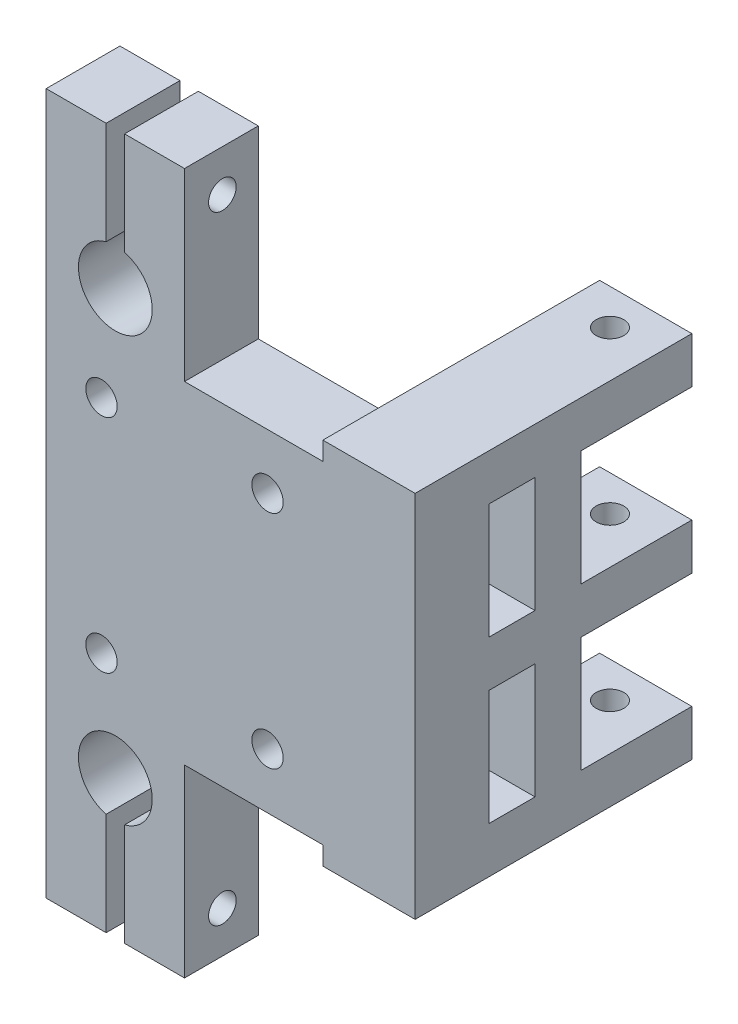
SolidWorks part; units mm, degrees
ref_plane "前视基准面" through (0, 0, 0) normal (0, 0, 1) x (1, 0, 0)
ref_plane "上视基准面" through (0, 0, 0) normal (0, 1, 0) x (1, 0, 0)
ref_plane "右视基准面" through (0, 0, 0) normal (1, 0, 0) x (0, 0, -1)
sketch "草图1" plane through (0, 0, 0) normal (0, 0, 1) x (1, 0, 0)
  line L0 (-18.375, -1.625) -> (11.625, -1.625) construction
  line L1 (-18.375, 16.375) -> (11.625, 16.375)
  line L2 (-18.375, 16.375) -> (-18.375, -19.625)
  line L3 (-18.375, -19.625) -> (11.625, -19.625)
  line L4 (11.625, 16.375) -> (11.625, -19.625)
  line L5 (-3.375, 16.375) -> (-3.375, -19.625) construction
  circle A0 centre (-12.375, 10.375) radius 1.7
  circle A1 centre (-12.375, -13.625) radius 1.7
  circle A2 centre (5.625, -13.625) radius 1.7
  circle A3 centre (5.625, 10.375) radius 1.7
  point P6 (-12.375, -1.625)
  point P10 (-12.375, -1.625)
  dimension "D1" = 36
  dimension "D2" = 30
  dimension "D3" = 6
  dimension "D4" = 24
extrude "凸台-拉伸1" add sketch "草图1" along normal blind 8
sketch "草图2" plane through (0, 0, 0) normal (0, 0, -1) x (-1, 0, 0)
  line L0 (3.375, 16.375) -> (3.375, -19.625) construction
  line L1 (-11.625, 16.375) -> (18.375, 16.375) construction
  line L2 (18.375, -19.625) -> (-11.625, -19.625) construction
  line L3 (-11.625, -1.625) -> (18.375, -1.625) construction
  line L4 (-11.625, -19.625) -> (-11.625, 16.375) construction
  line L5 (18.375, 16.375) -> (18.375, -19.625) construction
  circle A0 centre (12.375, 10.375) radius 3.75
  circle A1 centre (-5.625, 10.375) radius 3.75
  circle A2 centre (12.375, -13.625) radius 3.75
  circle A3 centre (-5.625, -13.625) radius 3.75
extrude "切除-拉伸1" cut sketch "草图2" against normal blind 4.5
sketch "草图3" plane through (0, 0, 8) normal (0, 0, 1) x (1, 0, 0)
  line L0 (-18.375, -1.625) -> (11.625, -1.625) construction
  line L1 (-18.375, 16.375) -> (-3.375, 16.375)
  line L2 (-18.375, 16.375) -> (-18.375, 36.375)
  line L3 (-18.375, 36.375) -> (-3.375, 36.375)
  line L4 (-3.375, 16.375) -> (-3.375, 36.375)
  line L5 (-18.375, 16.375) -> (-18.375, -19.625) construction
  line L6 (11.625, -19.625) -> (11.625, 16.375) construction
  line L7 (-18.375, -39.625) -> (-3.375, -39.625)
  line L8 (-3.375, -19.625) -> (-3.375, -39.625)
  line L9 (-18.375, -19.625) -> (-3.375, -19.625)
  line L10 (-18.375, -19.625) -> (-18.375, -39.625)
  line L11 (-10.875, 36.375) -> (-10.875, -39.625) construction
  line L12 (-10.875, 21.375) -> (-10.875, -24.625)
  circle A0 centre (-10.875, 21.375) radius 4
  circle A1 centre (-10.875, -24.625) radius 4
  point P20 (-10.875, -1.625)
  dimension "D1" = 20
  dimension "D2" = 15
  dimension "D3" = 46
sketch "草图4" plane through (0, 16.375, 0) normal (0, 1, 0) x (1, 0, 0)
  line L0 (11.625, -4) -> (-18.375, -4) construction
  line L1 (11.625, -8) -> (11.625, 0) construction
  line L2 (-18.375, -8) -> (-18.375, 0) construction
extrude "凸台-拉伸4" add sketch "草图3" against normal blind 8
sketch "草图8" plane through (0, 0, 8) normal (0, 0, 1) x (1, 0, 0)
  line L0 (11.625, -19.625) -> (11.625, 16.375) construction
  line L1 (11.625, -1.625) -> (11.625, 18.375) construction
  line L3 (11.625, 18.375) -> (21.625, 18.375)
  line L4 (11.625, 18.375) -> (11.625, -21.625)
  line L5 (11.625, -21.625) -> (21.625, -21.625)
  line L6 (21.625, 18.375) -> (21.625, -21.625)
  dimension "D1" = 20
  dimension "D2" = 40
  dimension "D3" = 10
extrude "凸台-拉伸5" add sketch "草图8" against normal blind 30
sketch "草图10" plane through (11.625, 0, 0) normal (-1, 0, 0) x (0, 0, 1)
  line L0 (-22, -1.625) -> (0, -1.625) construction
  line L1 (-22, 18.375) -> (-22, -21.625) construction
  line L2 (0, -19.625) -> (0, 16.375) construction
  line L3 (0, 0.875) -> (0, -4.125)
  line L4 (0, -16.625) -> (-5, -16.625)
  line L5 (0, 0.875) -> (-5, 0.875)
  line L6 (0, 0.875) -> (0, 13.375)
  line L7 (0, 13.375) -> (-5, 13.375)
  line L8 (-5, 0.875) -> (-5, 13.375)
  line L9 (-5, -4.125) -> (-5, -16.625)
  line L10 (0, -4.125) -> (-5, -4.125)
  line L11 (0, -4.125) -> (0, -16.625)
  line L12 (-5, 0.875) -> (-10, 0.875) construction
  line L13 (-10, -16.625) -> (-22, -16.625)
  line L14 (-10, 0.875) -> (-22, 0.875)
  line L15 (-10, 0.875) -> (-10, 13.375)
  line L16 (-10, 13.375) -> (-22, 13.375)
  line L17 (-22, 0.875) -> (-22, 13.375)
  line L18 (-22, -4.125) -> (-22, -16.625)
  line L19 (-10, -4.125) -> (-22, -4.125)
  line L20 (-10, -4.125) -> (-10, -16.625)
  point P10 (0, -1.625)
  line M15 (-22, 18.375) -> (-22, -21.625)
  line M19 (0, -19.625) -> (0, 16.375)
  dimension "D1" = 5
  dimension "D2" = 12.5
  dimension "D3" = 5
  dimension "D4" = 5
extrude "切除-拉伸4" cut sketch "草图10" against normal blind 30 contours L15 L16 L14 M15 | L8 L5 L7 M19 | L10 L9 L4 M19 | L20 L19 L13 M15
sketch "草图11" plane through (0, 18.375, 0) normal (0, 1, 0) x (1, 0, 0)
  circle A0 centre (16.6218, 18.1233) radius 1.5
extrude "切除-拉伸5" cut sketch "草图11" against normal blind 47 contours A0
sketch "草图12" plane through (0, 0, 0) normal (0, 0, -1) x (-1, 0, 0)
  line L0 (10.875, 36.375) -> (10.875, 25.375) construction
  line L1 (18.375, 36.375) -> (3.375, 36.375) construction
  line L2 (18.375, -39.625) -> (3.375, -39.625) construction
  line L3 (9.875, 49.2961) -> (11.875, 49.2961)
  line L4 (9.875, 49.2961) -> (9.875, 23.4539)
  line L5 (9.875, 23.4539) -> (11.875, 23.4539)
  line L6 (11.875, 49.2961) -> (11.875, 23.4539)
  line L7 (9.875, 49.2961) -> (11.875, 23.4539) construction
  line L8 (9.875, 23.4539) -> (11.875, 49.2961) construction
  line L9 (9.875, -24.2468) -> (11.875, -24.2468)
  line L10 (9.875, -24.2468) -> (9.875, -55.0032)
  line L11 (9.875, -55.0032) -> (11.875, -55.0032)
  line L12 (11.875, -24.2468) -> (11.875, -55.0032)
  line L13 (9.875, -24.2468) -> (11.875, -55.0032) construction
  line L14 (9.875, -55.0032) -> (11.875, -24.2468) construction
  circle A0 centre (10.875, 21.375) radius 4 construction
  point P11 (10.875, -39.625)
  dimension "D1" = 2
  dimension "D2" = 2
extrude "切除-拉伸6" cut sketch "草图12" against normal blind 10
sketch "草图13" plane through (-18.375, 0, 0) normal (-1, 0, 0) x (0, 0, 1)
  line L0 (8, -1.625) -> (0, -1.625) construction
  line L1 (8, 36.375) -> (8, -39.625) construction
  line L2 (0, 36.375) -> (0, -39.625) construction
  circle A0 centre (3.8925, 31.8681) radius 1.5
  circle A1 centre (3.8925, -35.1181) radius 1.5
  point P8 (-1.1537, -5.0918)
extrude "切除-拉伸7" cut sketch "草图13" against normal blind 40
